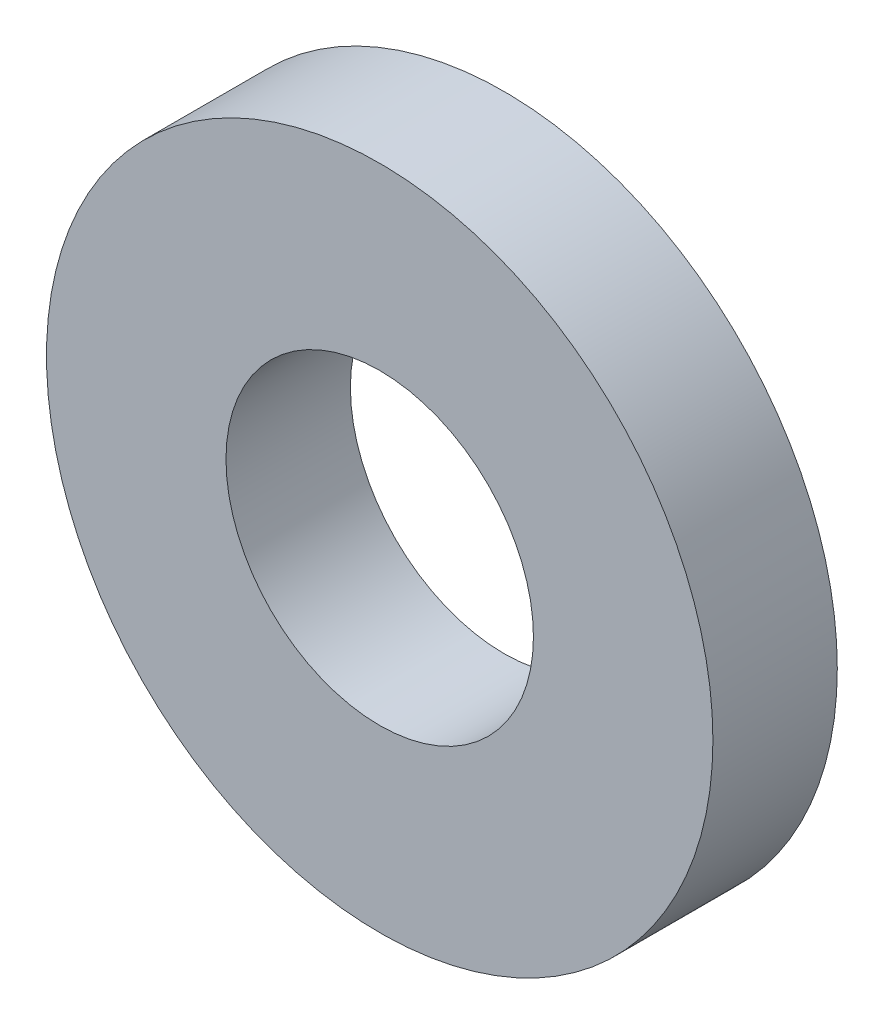
SolidWorks part; units mm, degrees
ref_plane "Front Plane" through (0, 0, 0) normal (0, 0, 1) x (1, 0, 0)
ref_plane "Top Plane" through (0, 0, 0) normal (0, 1, 0) x (1, 0, 0)
ref_plane "Right Plane" through (0, 0, 0) normal (1, 0, 0) x (0, 0, -1)
sketch "Sketch1" plane through (0, 0, 0) normal (0, 0, 1) x (1, 0, 0)
  circle A0 centre (0, 0) radius 4.7625
  circle A1 centre (0, 0) radius 2.1971
  point P5 (0, -4.7625)
  dimension "OD" = 9.525
  dimension "ID" = 4.3942
sketch "Sketch2" plane through (0, 0, 0) normal (1, 0, 0) x (0, 0, -1)
  line L0 (-0.889, 0) -> (0.889, 0) construction
  point P0 (-0.889, -4.7625)
  point P4 (0, 0)
  point P6 (0.889, -4.7625)
  dimension "Thickness Range" = 1.778
sketch "Sketch3" plane through (0, 0, 0) normal (0, 0, 1) x (1, 0, 0)
  circle A0 centre (0, 0) radius 4.7625 construction
  circle A1 centre (0, 0) radius 2.1971 construction
  circle A2 centre (0, 0) radius 4.7625
  circle A3 centre (0, 0) radius 2.1971
extrude "Boss-Extrude1" add sketch "Sketch3" along normal up to vertex (0.889 mm away) and the other way up to vertex (0.889 mm away) up to point (0, -4.7625, 0.889) other way up to point (0, -4.7625, -0.889)
